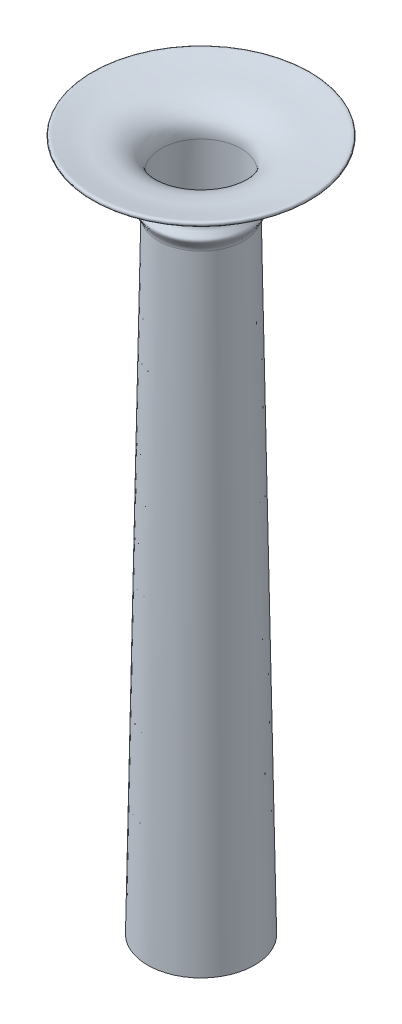
SolidWorks part; units mm, degrees
ref_plane "Front Plane" through (0, 0, 0) normal (0, 0, 1) x (1, 0, 0)
ref_plane "Top Plane" through (0, 0, 0) normal (0, 1, 0) x (1, 0, 0)
ref_plane "Right Plane" through (0, 0, 0) normal (1, 0, 0) x (0, 0, -1)
sketch "Sketch1" plane through (0, 0, 0) normal (0, 0, 1) x (1, 0, 0)
  line L0 (0, 0) -> (-12.5, 0) construction
  line L1 (0, 0) -> (0, 903.7082) construction
  line L3 (-12.5, 0) -> (-9.6968, 160.5946)
  line L10 (-10.3618, 151.1442) -> (-13, 0)
  line L11 (-13, 0) -> (-12.5, 0)
  spline S0 degree 3 poles (-9.6968, 160.5946) (-9.6672, 162.293) (-10.4865, 164.3069) (-16.1278, 167.8996) (-20.2233, 166.8105) (-26.497, 168.7595) (-26.5229, 167.6924) (-25.7428, 167.273) (-24.3744, 167.7423) (-20.9433, 166.7276) (-15.6414, 167.3977) (-9.09, 162.4831) (-10.882, 159.0609) (-10.2705, 157.5442) (-10.0688, 155.5802) (-12.1203, 154.3719) (-10.9632, 152.7271) (-10.351, 151.7583) (-10.3618, 151.1442) knots 0 0 0 0 0.082451 0.139496 0.37669 0.407777 0.41658 0.430442 0.453143 0.50108 0.637253 0.800464 0.82602 0.852886 0.896024 0.93407 0.96031 1 1 1 1
  point P6 (-10.2539, 157.6261)
  point P8 (-10.4653, 145.2152)
  point P10 (-11.6616, 145.2152)
  point P11 (-11.1617, 146.6735)
  point P13 (-14.5081, 149.8718)
  point P15 (-12.1982, 152.1817)
  point P18 (-10.4806, 155.38)
  point P20 (-10.3325, 160.2959)
  point P22 (-10.6879, 159.0817)
  point P24 (-10.4214, 157.7787)
  point P27 (-10.5398, 155.6465)
  point P28 (-11.6651, 154.1362)
  point P29 (-11.7836, 150.8195)
  point P30 (-10.396, 149.1825)
  point P31 (-11.4579, 152.4186)
  point P33 (-10.3618, 151.1442)
  point P35 (-11.1321, 152.9516)
  point P37 (-16.4741, 166.1259)
  point P39 (-23.2636, 166.1259)
  point P41 (-25.3168, 165.1693)
  point P43 (-26.81, 166.1492)
  point P44 (-26.95, 167.5025)
  point P45 (-26.5067, 166.9425)
  point P46 (-25.2468, 166.4525)
  point P47 (-23.0536, 166.6625)
  point P48 (-25.1301, 166.7559)
  point P49 (-25.9001, 167.4325)
  point P50 (-26.46, 167.8291)
  point P51 (-24.7802, 167.5258)
  point P52 (-22.4237, 167.2458)
  point P53 (-15.7509, 166.2892)
  dimension "D1" = 12.5
  dimension "D7" = 89
  dimension "D8" = 0.5
revolve "Revolve1" add sketch "Sketch1" angle 360 about L1
